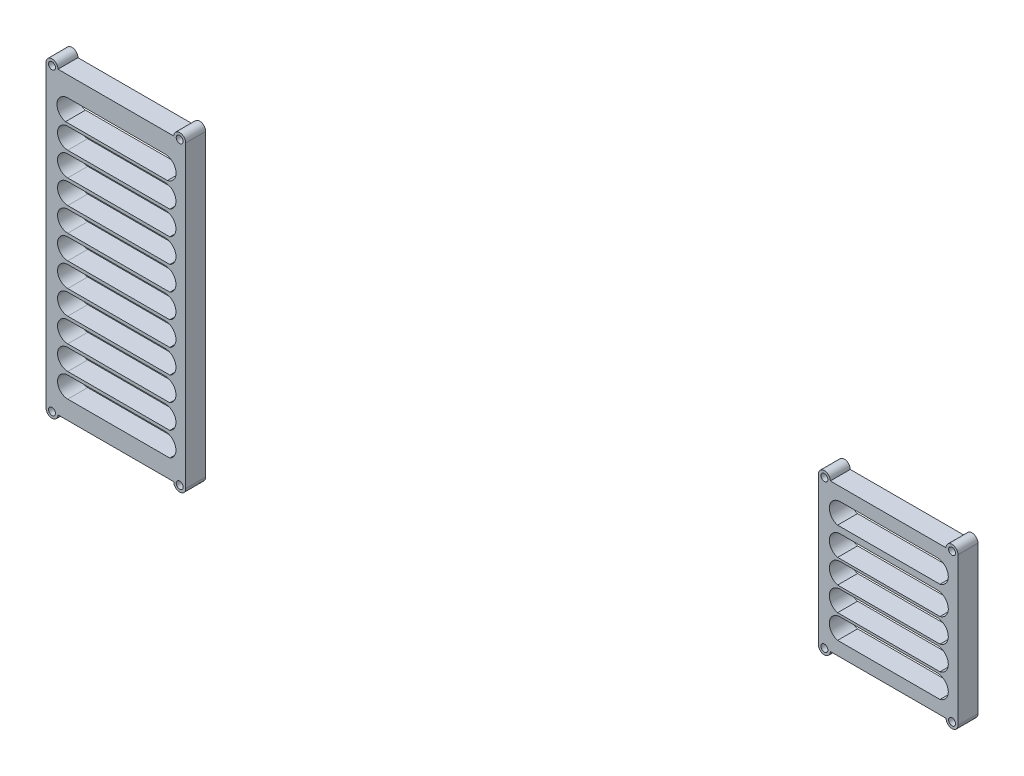
SolidWorks part; units mm, degrees
ref_plane "Front Plane" through (0, 0, 0) normal (0, 0, 1) x (1, 0, 0)
ref_plane "Top Plane" through (0, 0, 0) normal (0, 1, 0) x (1, 0, 0)
ref_plane "Right Plane" through (0, 0, 0) normal (1, 0, 0) x (0, 0, -1)
sketch "Sketch1" plane through (0, 0, 0) normal (0, 0, 1) x (1, 0, 0)
  line L1 (-51.1808, 47.1225) -> (-22.1808, 47.1225)
  line L2 (-54.1808, 47.1225) -> (-54.1808, -27.8775)
  line L3 (-51.1808, -27.8775) -> (-22.1808, -27.8775)
  line L4 (-19.1808, 47.1225) -> (-19.1808, -27.8775)
  line L5 (-66.8168, 9.6225) -> (11.6258, 9.6225) construction
  line L6 (-48.6808, 35.9812) -> (-24.3739, 35.9812)
  line L7 (-48.6808, 42.1225) -> (-24.3421, 42.1225)
  line L9 (-49.2897, 36.6907) -> (-23.7333, 36.6907)
  line L10 (-48.7307, 30.7642) -> (-23.1589, 30.7642)
  line L11 (-48.6808, 29.9812) -> (-24.3739, 29.9812)
  line L12 (-48.7307, 24.7642) -> (-23.1589, 24.7642)
  line L13 (-48.6808, 23.9812) -> (-24.3739, 23.9812)
  line L14 (-48.7307, 18.7642) -> (-23.1589, 18.7642)
  line L15 (-48.6808, 17.9812) -> (-24.3739, 17.9812)
  line L16 (-48.7307, 12.7642) -> (-23.1589, 12.7642)
  line L17 (-48.6808, 11.9812) -> (-24.3739, 11.9812)
  line L18 (-48.7307, 6.7642) -> (-23.1589, 6.7642)
  line L19 (-48.6808, 5.9812) -> (-24.3739, 5.9812)
  line L20 (-48.7307, 0.7642) -> (-23.1589, 0.7642)
  line L21 (-48.6808, -0.0188) -> (-24.3739, -0.0188)
  line L22 (-48.7307, -5.2358) -> (-23.1589, -5.2358)
  line L23 (-48.6808, -6.0188) -> (-24.3739, -6.0188)
  line L24 (-48.7307, -11.2358) -> (-23.1589, -11.2358)
  line L25 (-48.6808, -12.0188) -> (-24.3739, -12.0188)
  line L26 (-48.7307, -17.2358) -> (-23.1589, -17.2358)
  line L27 (-48.6837, -18.0188) -> (-24.3768, -18.0188)
  line L28 (-48.7336, -23.2358) -> (-23.1617, -23.2358)
  line L30 (142.3192, 54.5319) -> (171.3192, 54.5319)
  line L31 (139.3192, 54.5319) -> (139.3192, 17.5319)
  line L32 (142.3192, 17.5319) -> (171.3192, 17.5319)
  line L33 (174.3192, 54.5319) -> (174.3192, 17.5319)
  line L35 (144.8192, 51.2819) -> (169.1261, 51.2819)
  line L36 (144.1467, 45.8653) -> (169.7985, 45.8653)
  line L37 (144.8192, 44.2819) -> (169.1261, 44.2819)
  line L38 (144.1467, 38.8653) -> (169.7985, 38.8653)
  line L39 (144.8192, 38.2819) -> (169.1261, 38.2819)
  line L40 (144.1467, 32.8653) -> (169.7985, 32.8653)
  line L41 (144.8192, 32.2819) -> (169.1261, 32.2819)
  line L42 (144.1467, 26.8653) -> (169.7985, 26.8653)
  line L43 (144.8192, 26.2819) -> (169.1261, 26.2819)
  line L44 (144.1467, 20.8653) -> (169.7985, 20.8653)
  arc A0 (-51.1808, 47.1225) -> (-54.1808, 47.1225) centre (-52.6808, 47.1225) ccw
  arc A1 (-19.1808, 47.1225) -> (-22.1808, 47.1225) centre (-20.6808, 47.1225) ccw
  arc A2 (-51.1808, -27.8775) -> (-54.1808, -27.8775) centre (-52.6808, -27.8775) cw
  arc A3 (-19.1808, -27.8775) -> (-22.1808, -27.8775) centre (-20.6808, -27.8775) cw
  arc A4 (-23.7333, 36.6907) -> (-24.3421, 42.1225) centre (-24.3421, 39.3725) ccw
  arc A5 (-48.6808, 42.1225) -> (-49.2897, 36.6907) centre (-48.6808, 39.3725) ccw
  arc A6 (-23.1589, 30.7642) -> (-24.3739, 35.9812) centre (-24.3739, 33.2312) ccw
  arc A7 (-48.6808, 35.9812) -> (-48.7307, 30.7642) centre (-48.6808, 33.3725) ccw
  arc A8 (-23.1589, 24.7642) -> (-24.3739, 29.9812) centre (-24.3739, 27.2312) ccw
  arc A9 (-48.6808, 29.9812) -> (-48.7307, 24.7642) centre (-48.6808, 27.3725) ccw
  arc A10 (-23.1589, 18.7642) -> (-24.3739, 23.9812) centre (-24.3739, 21.2312) ccw
  arc A11 (-48.6808, 23.9812) -> (-48.7307, 18.7642) centre (-48.6808, 21.3725) ccw
  arc A12 (-23.1589, 12.7642) -> (-24.3739, 17.9812) centre (-24.3739, 15.2312) ccw
  arc A13 (-48.6808, 17.9812) -> (-48.7307, 12.7642) centre (-48.6808, 15.3725) ccw
  arc A14 (-23.1589, 6.7642) -> (-24.3739, 11.9812) centre (-24.3739, 9.2312) ccw
  arc A15 (-48.6808, 11.9812) -> (-48.7307, 6.7642) centre (-48.6808, 9.3725) ccw
  arc A16 (-23.1589, 0.7642) -> (-24.3739, 5.9812) centre (-24.3739, 3.2312) ccw
  arc A17 (-48.6808, 5.9812) -> (-48.7307, 0.7642) centre (-48.6808, 3.3725) ccw
  arc A18 (-23.1589, -5.2358) -> (-24.3739, -0.0188) centre (-24.3739, -2.7688) ccw
  arc A19 (-48.6808, -0.0188) -> (-48.7307, -5.2358) centre (-48.6808, -2.6275) ccw
  arc A20 (-23.1589, -11.2358) -> (-24.3739, -6.0188) centre (-24.3739, -8.7688) ccw
  arc A21 (-48.6808, -6.0188) -> (-48.7307, -11.2358) centre (-48.6808, -8.6275) ccw
  arc A22 (-23.1589, -17.2358) -> (-24.3739, -12.0188) centre (-24.3739, -14.7688) ccw
  arc A23 (-48.6808, -12.0188) -> (-48.7307, -17.2358) centre (-48.6808, -14.6275) ccw
  arc A24 (-23.1617, -23.2358) -> (-24.3768, -18.0188) centre (-24.3768, -20.7688) ccw
  arc A25 (-48.6837, -18.0188) -> (-48.7336, -23.2358) centre (-48.6837, -20.6275) ccw
  arc A26 (169.7985, 45.8653) -> (169.1261, 51.2819) centre (169.1261, 48.5319) ccw
  arc A27 (144.8192, 51.2819) -> (144.1467, 45.8653) centre (144.8192, 48.5319) ccw
  arc A28 (169.7985, 38.8653) -> (169.1261, 44.2819) centre (169.1261, 41.5319) ccw
  arc A29 (144.8192, 44.2819) -> (144.1467, 38.8653) centre (144.8192, 41.5319) ccw
  arc A30 (169.7985, 32.8653) -> (169.1261, 38.2819) centre (169.1261, 35.5319) ccw
  arc A31 (144.8192, 38.2819) -> (144.1467, 32.8653) centre (144.8192, 35.5319) ccw
  arc A32 (169.7985, 26.8653) -> (169.1261, 32.2819) centre (169.1261, 29.5319) ccw
  arc A33 (144.8192, 32.2819) -> (144.1467, 26.8653) centre (144.8192, 29.5319) ccw
  arc A34 (169.7985, 20.8653) -> (169.1261, 26.2819) centre (169.1261, 23.5319) ccw
  arc A35 (144.8192, 26.2819) -> (144.1467, 20.8653) centre (144.8192, 23.5319) ccw
  arc A36 (142.3192, 54.5319) -> (139.3192, 54.5319) centre (140.8192, 54.5319) ccw
  arc A37 (174.3192, 54.5319) -> (171.3192, 54.5319) centre (172.8192, 54.5319) ccw
  arc A38 (139.3192, 17.5319) -> (142.3192, 17.5319) centre (140.8192, 17.5319) ccw
  arc A39 (171.3192, 17.5319) -> (174.3192, 17.5319) centre (172.8192, 17.5319) ccw
  circle A40 centre (-20.6808, -27.8775) radius 0.875
  circle A41 centre (-52.6808, -27.8775) radius 0.875
  circle A42 centre (-20.6808, 47.1225) radius 0.875
  circle A43 centre (-52.6808, 47.1225) radius 0.875
  circle A44 centre (140.8192, 54.5319) radius 0.875
  circle A45 centre (172.8192, 54.5319) radius 0.875
  circle A46 centre (172.8192, 17.5319) radius 0.875
  circle A47 centre (140.8192, 17.5319) radius 0.875
  dimension "D4" = 3
  dimension "D6" = 3
  dimension "D13" = 5.5
  dimension "D16" = 5.5
  dimension "D48" = 3
  dimension "D49" = 3
  dimension "D50" = 3
  dimension "D51" = 3
  dimension "D7" = 1.75
  dimension "D36" = 1.75
  dimension "D37" = 1.75
  dimension "D41" = 1.75
  dimension "D42" = 1.75
  dimension "D43" = 1.75
  dimension "D44" = 1.75
  dimension "D52" = 1.75
  dimension "D1" = 35
  dimension "D2" = 75
  dimension "D8" = 37.5
  dimension "D9" = 2.75
  dimension "D10" = 6
  dimension "D11" = 5
  dimension "D12" = 6
  dimension "D14" = 2.75
  dimension "D15" = 5.5
  dimension "D17" = 5.5
  dimension "6" = 6
  dimension "D18" = 5.5
  dimension "D19" = 5.5
  dimension "D20" = 5.5
  dimension "D21" = 6
  dimension "D22" = 6
  dimension "D23" = 6
  dimension "D24" = 6
  dimension "D25" = 6
  dimension "D26" = 6
  dimension "D27" = 5.5
  dimension "D28" = 5.5
  dimension "D29" = 5.5
  dimension "D30" = 5.5
  dimension "D31" = 5.5
  dimension "D32" = 6
  dimension "D33" = 5.4971
  dimension "D34" = 35
  dimension "D35" = 6
  dimension "D38" = 5.5
  dimension "D39" = 6
  dimension "D40" = 7
  dimension "D45" = 6
  dimension "D46" = 6
  dimension "D47" = 6
extrude "Boss-Extrude2" add sketch "Sketch1" along normal blind 5 contours L2 L5 A15 L17 A14 L4 A1 L1 A43 A5 L7 A4 L9 A7 L6 A6 L10 A9 L11 A8 L12 A11 L13 A10 L14 A13 L15 A12 L16 A42 | L5 L2 A2 L3 A3 L4 A14 L18 A15 A41 A40 A25 L27 A24 L28 A23 L25 A22 L26 A21 L23 A20 L24 A19 L21 A18 L22 A17 L19 A16 L20 | L32 A39 L33 A37 L30 A36 L31 A38 A47 A46 A45 A44 A27 L35 A26 L36 A29 L37 A28 L38 A31 L39 A30 L40 A33 L41 A32 L42 A35 L43 A34 L44 | L37 A29 L38 A28
